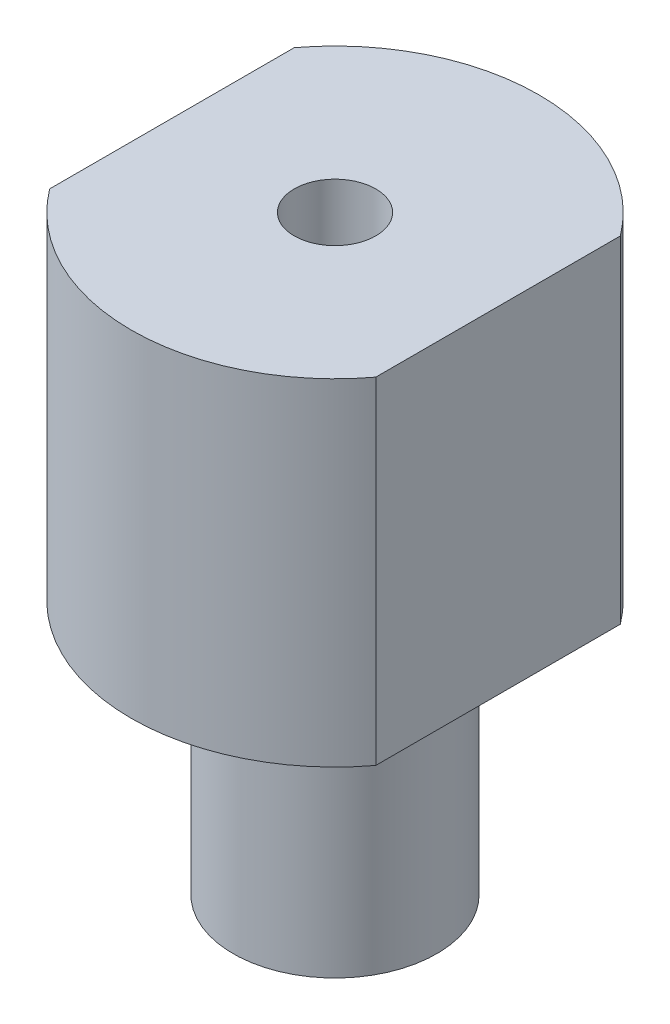
SolidWorks part; units mm, degrees
ref_plane "前视基准面" through (0, 0, 0) normal (0, 0, 1) x (1, 0, 0)
ref_plane "上视基准面" through (0, 0, 0) normal (0, 1, 0) x (1, 0, 0)
ref_plane "右视基准面" through (0, 0, 0) normal (1, 0, 0) x (0, 0, -1)
other "Configuration Table"
sketch "草图1" plane through (0, 0, 0) normal (0, 1, 0) x (1, 0, 0)
  line L2 (-16, 12) -> (-16, -12)
  line L3 (16, 12) -> (16, -12)
  arc A0 (-16, -12) -> (16, -12) centre (0, 0) ccw
  arc A1 (16, 12) -> (-16, 12) centre (0, 0) ccw
  dimension "D1" = 40
extrude "凸台-拉伸1" add sketch "草图1" along normal blind 33
sketch "草图2" plane through (0, 0, 0) normal (0, -1, 0) x (1, 0, 0)
  circle A0 centre (0, 0) radius 10
  dimension "D1" = 20
extrude "凸台-拉伸2" add sketch "草图2" along normal blind 25
sketch "草图3" plane through (0, 33, 0) normal (0, 1, 0) x (1, 0, 0)
  circle A0 centre (0, 0) radius 4
extrude "切除-拉伸1" cut sketch "草图3" against normal blind 8
sketch "草图4" plane through (0, -25, 0) normal (0, -1, 0) x (1, 0, 0)
  circle A0 centre (0, 0) radius 3.4619
extrude "切除-拉伸2" cut sketch "草图4" against normal blind 25
